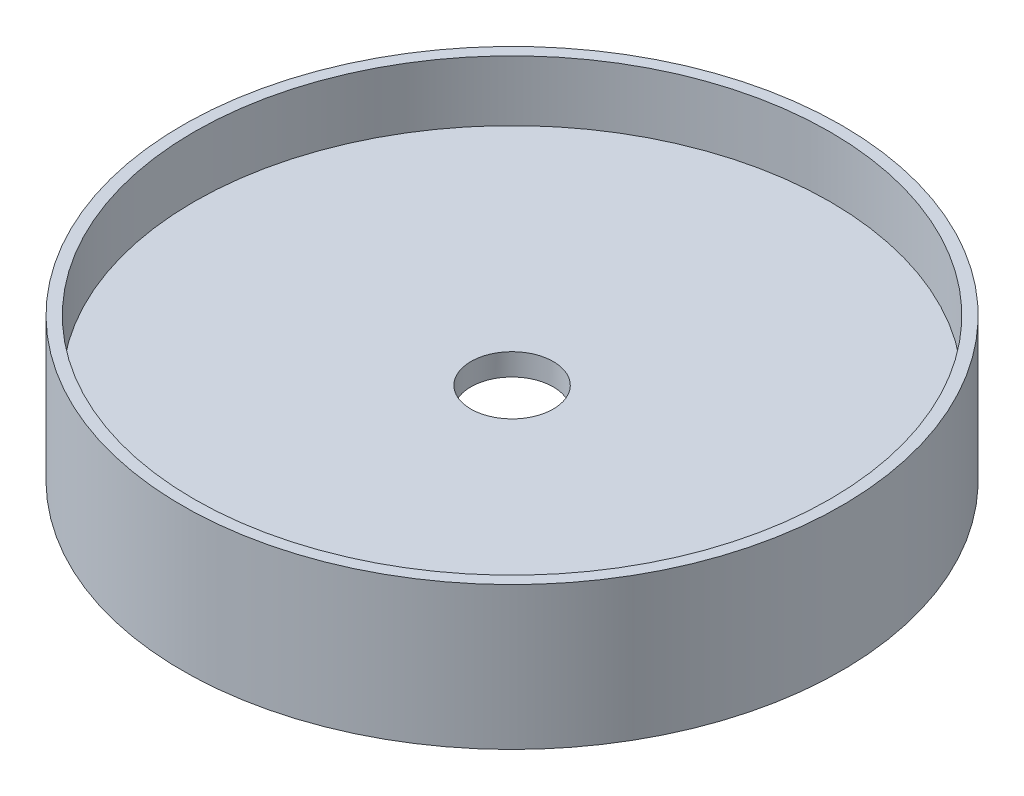
SolidWorks part; units mm, degrees
ref_plane "Front Plane" through (0, 0, 0) normal (0, 0, 1) x (1, 0, 0)
ref_plane "Top Plane" through (0, 0, 0) normal (0, 1, 0) x (1, 0, 0)
ref_plane "Right Plane" through (0, 0, 0) normal (1, 0, 0) x (0, 0, -1)
sketch "Sketch1" plane through (0, 0, 0) normal (0, 0, 1) x (1, 0, 0)
  line L0 (289.5, 20) -> (289.5, 75)
  line L1 (0, 0) -> (289.5, 0)
  line L2 (0, 0) -> (0, 20)
  line L3 (0, 20) -> (289.5, 20)
  line L5 (289.5, -55) -> (300, -55)
  line L6 (289.5, -55) -> (289.5, 0)
  line L7 (289.5, 75) -> (300, 75)
  line L8 (300, -55) -> (300, 75)
  dimension "D1" = 130
  dimension "D2" = 300
  dimension "D3" = 10.5
  dimension "D4" = 20
revolve "Revolve1" add sketch "Sketch1" angle 360 about L2
sketch "Sketch2" plane through (0, 20, 0) normal (0, 1, 0) x (1, 0, 0)
  circle A0 centre (0, 0) radius 37.5
  dimension "D1" = 75
extrude "Cut-Extrude1" cut sketch "Sketch2" against normal through all contours A0
